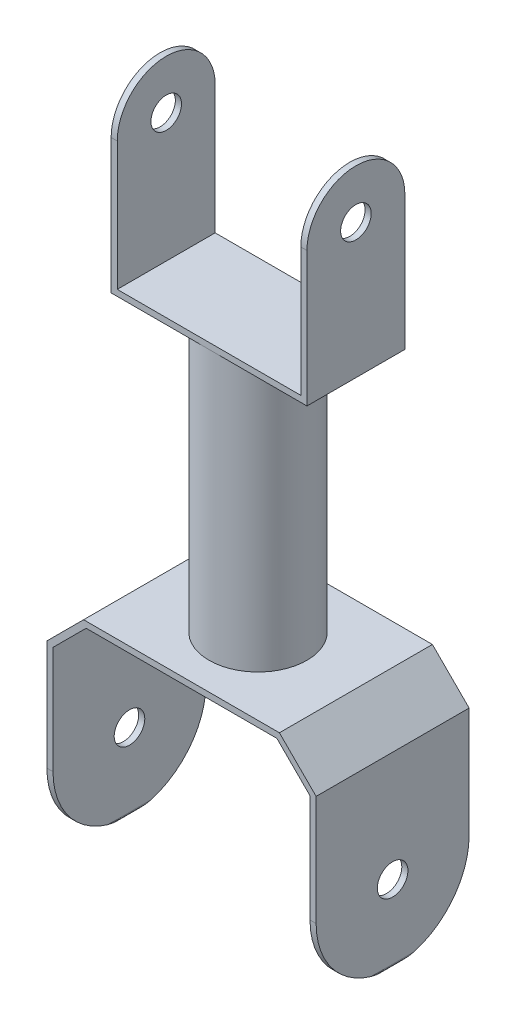
SolidWorks part; units mm, degrees
ref_plane "Front Plane" through (0, 0, 0) normal (0, 0, 1) x (1, 0, 0)
ref_plane "Top Plane" through (0, 0, 0) normal (0, 1, 0) x (1, 0, 0)
ref_plane "Right Plane" through (0, 0, 0) normal (1, 0, 0) x (0, 0, -1)
sketch "Sketch1" plane through (0, 0, 0) normal (0, 0, 1) x (1, 0, 0)
  line L0 (0, 0) -> (0, 110) construction
  line L1 (-22, 0) -> (22, 0) construction
  line L2 (-16, 110) -> (16, 110) construction
  line L3 (-16, 110) -> (-16, 80)
  line L5 (16, 80) -> (16, 110)
  line L6 (-16, 80) -> (16, 80)
  line L7 (-22, 0) -> (-22, 30)
  line L8 (-22, 30) -> (-16, 36)
  line L9 (-16, 36) -> (16, 36)
  line L10 (16, 36) -> (22, 30)
  line L11 (22, 30) -> (22, 0)
  line L12 (-15, 110) -> (-15, 81)
  line L13 (-15, 81) -> (15, 81)
  line L14 (15, 81) -> (15, 110)
  line L15 (-21, 0) -> (-21, 29.5858)
  line L16 (-21, 29.5858) -> (-15.5858, 35)
  line L17 (-15.5858, 35) -> (15.5858, 35)
  line L18 (15.5858, 35) -> (21, 29.5858)
  line L19 (21, 29.5858) -> (21, 0)
  arc A0 (-21, 0) -> (-22, 0) centre (-21.5, 0) cw
  arc A1 (21, 0) -> (22, 0) centre (21.5, 0) ccw
  arc A2 (-16, 110) -> (-15, 110) centre (-15.5, 110) cw
  arc A3 (15, 110) -> (16, 110) centre (15.5, 110) cw
  point P6 (0, 0)
  point P9 (0, 110)
  dimension "D1" = 110
  dimension "D2" = 1
  dimension "D3" = 1
extrude "Boss-Extrude1" add sketch "Sketch1" along normal mid plane 25
sketch "Sketch3" plane through (22, 0, 0) normal (1, 0, 0) x (0, 0, -1)
  line L0 (0, 110) -> (0, 80) construction
  line L1 (-12.5, 110) -> (12.5, 110) construction
  line L2 (-12.5, 80) -> (12.5, 80) construction
  line L3 (8, 80) -> (8, 102)
  line L4 (-8, 80) -> (-8, 102)
  line L5 (0, 110) -> (0, 102) construction
  line L6 (-8, 80) -> (-12.5, 80)
  line L7 (-12.5, 80) -> (-12.5, 110.5)
  line L8 (-12.5, 110.5) -> (12.5, 110.5)
  line L9 (12.5, 110.5) -> (12.5, 80)
  line L10 (12.5, 80) -> (8, 80)
  line L11 (0, 36) -> (0, -0.5) construction
  line L12 (-12.5, 36) -> (12.5, 36) construction
  line L13 (-12.5, -0.5) -> (12.5, -0.5) construction
  line L14 (0, -0.5) -> (0, 12) construction
  line L15 (-12.5, 12) -> (-12.5, 36)
  line L17 (12.5, 36) -> (12.5, 12)
  line L18 (-12.5, 36) -> (-17.5, 36)
  line L19 (-17.5, 36) -> (-17.5, -4)
  line L20 (-17.5, -4) -> (17.5, -4)
  line L21 (17.5, -4) -> (17.5, 36)
  line L22 (17.5, 36) -> (12.5, 36)
  arc A0 (8, 102) -> (-8, 102) centre (0, 102) ccw
  circle A1 centre (0, 102) radius 2.5
  arc A2 (-12.5, 12) -> (12.5, 12) centre (0, 12) ccw
  circle A3 centre (0, 12) radius 2.5
extrude "Cut-Extrude1" cut sketch "Sketch3" against normal through all both and the other way through all
sketch "Sketch4" plane through (0, 36, 0) normal (0, 1, 0) x (1, 0, 0)
  circle A0 centre (0, 0) radius 8
  circle A1 centre (0, 0) radius 6.0004
extrude "Boss-Extrude2" add sketch "Sketch4" along normal blind 44
